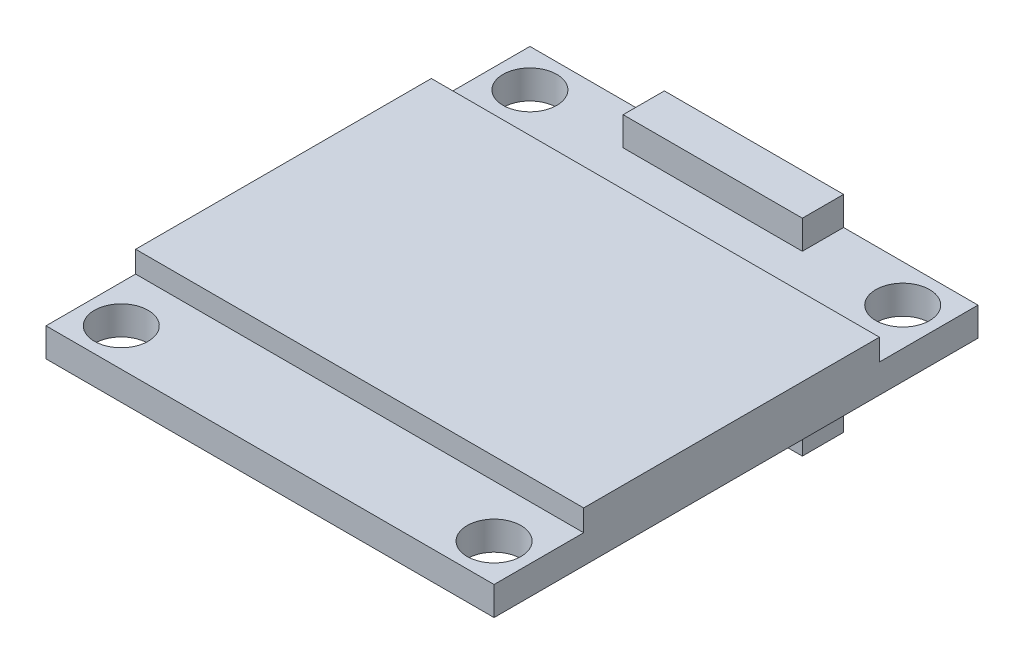
SolidWorks part; units mm, degrees
ref_plane "前视基准面" through (0, 0, 0) normal (0, 0, 1) x (1, 0, 0)
ref_plane "上视基准面" through (0, 0, 0) normal (0, 1, 0) x (1, 0, 0)
ref_plane "右视基准面" through (0, 0, 0) normal (1, 0, 0) x (0, 0, -1)
other "Configuration Table"
sketch "草图1" plane through (0, 0, 0) normal (0, 1, 0) x (1, 0, 0)
  line L1 (0, 0) -> (25, 0)
  line L2 (0, 0) -> (0, 27)
  line L3 (0, 27) -> (25, 27)
  line L4 (25, 0) -> (25, 27)
  dimension "D1" = 27
  dimension "D2" = 25
extrude "凸台-拉伸1" add sketch "草图1" along normal blind 1.6
sketch "草图2" plane through (0, 1.6, 0) normal (0, 1, 0) x (1, 0, 0)
  line L0 (0, 27) -> (0, 0) construction
  line L1 (0, 21.5) -> (25, 21.5)
  line L2 (0, 21.5) -> (0, 5)
  line L3 (0, 5) -> (25, 5)
  line L4 (25, 21.5) -> (25, 5)
  line L5 (25, 0) -> (25, 27) construction
  line L6 (25, 27) -> (0, 27) construction
  dimension "D1" = 5.5
  dimension "D2" = 16.5
extrude "凸台-拉伸2" add sketch "草图2" along normal blind 1.2
sketch "草图3" plane through (0, 1.6, 0) normal (0, 1, 0) x (1, 0, 0)
  line L0 (0, 27) -> (0, 21.5) construction
  line L1 (25, 27) -> (0, 27) construction
  line L2 (12.5, 27) -> (12.5, 0) construction
  line L3 (0, 0) -> (25, 0) construction
  line L4 (26.522, 13.5) -> (-3.1759, 13.5) construction
  circle A0 centre (2.1, 24.9) radius 1.5
  circle A1 centre (22.9, 24.9) radius 1.5
  circle A2 centre (22.9, 2.1) radius 1.5
  circle A3 centre (2.1, 2.1) radius 1.5
  dimension "D1" = 3
  dimension "D2" = 2.1
  dimension "D3" = 2.1
  dimension "D4" = 13.5
extrude "切除-拉伸1" cut sketch "草图3" against normal through all
sketch "草图5" plane through (0, 1.6, 0) normal (0, 1, 0) x (1, 0, 0)
  line L0 (25, 27) -> (0, 27) construction
  line L1 (7.5, 27) -> (17.5, 27)
  line L2 (7.5, 27) -> (7.5, 24.7)
  line L3 (7.5, 24.7) -> (17.5, 24.7)
  line L4 (17.5, 27) -> (17.5, 24.7)
  line L5 (12.5, 0) -> (12.5, 27) construction
  line L6 (0, 0) -> (25, 0) construction
  dimension "D1" = 10
  dimension "D2" = 2.3
extrude "凸台-拉伸4" add sketch "草图5" along normal blind 1.6 and the other way offset from surface (9.9 mm away) 8.3 other way up to face at (2.1, 0, -3.6)
